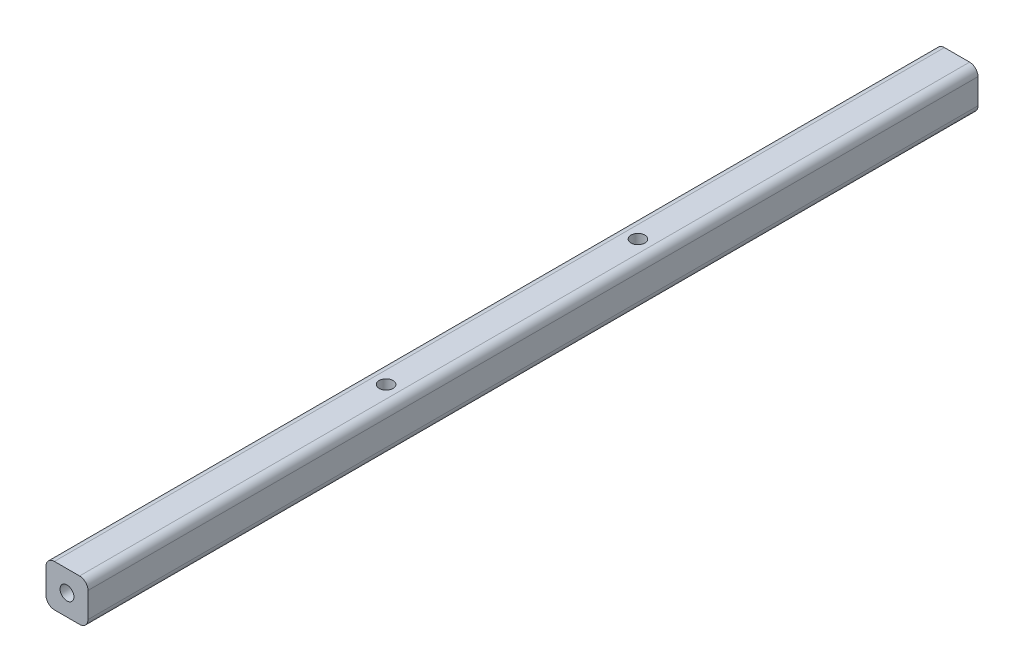
SolidWorks part; units mm, degrees
material "Alliage 1060"
ref_plane "Face" through (0, 0, 0) normal (0, 0, 1) x (1, 0, 0)
ref_plane "Dessus" through (0, 0, 0) normal (0, 1, 0) x (1, 0, 0)
ref_plane "Droite" through (0, 0, 0) normal (1, 0, 0) x (0, 0, -1)
sketch "Esquisse1" plane through (0, 0, 0) normal (0, 0, 1) x (1, 0, 0)
  line L1 (-5, 5) -> (5, 5)
  line L2 (-5, 5) -> (-5, -5)
  line L3 (-5, -5) -> (5, -5)
  line L4 (5, 5) -> (5, -5)
extrude "Boss.-Extru.1" add sketch "Esquisse1" along normal mid plane 212
hole_wizard "Trou taraudé M41" positions "Esquisse3" profile "Esquisse2" tap size "M4" standard "Iso"
sketch "Esquisse3" plane through (0, 0, 106) normal (0, 0, 1) x (1, 0, 0)
  point P0 (0, 0)
sketch "Esquisse2" plane through (0, 0, 106) normal (1, 0, 0) x (0, -1, 0)
  line L0 (0, 0) -> (0, 12.4914)
  line L1 (0, 12.4914) -> (1.65, 11.5)
  line L2 (1.65, 11.5) -> (1.65, 0)
  line L5 (1.65, 0) -> (0, 0)
  line L10 (0, 12.4914) -> (-1.65, 11.5) construction
  line L11 (0, -6.35) -> (0, 107.95) construction
  dimension "Diamètre du trou pour taraudage" = 3.3
  dimension "Profondeur du trou pour taraudage" = 11.5
  dimension "Angle de pointe" = 118
cosmetic thread "Filetage de perçage1" parameters "D1"=8, "D2"=4
hole_wizard "Trou taraudé M42" positions "Esquisse5" profile "Esquisse4" tap size "M4" standard "Iso"
sketch "Esquisse5" plane through (0, 0, -106) normal (0, 0, -1) x (-1, 0, 0)
  point P0 (0, 0)
sketch "Esquisse4" plane through (0, 0, -106) normal (1, 0, 0) x (0, 1, 0)
  line L0 (0, 0) -> (0, 12.4914)
  line L1 (0, 12.4914) -> (1.65, 11.5)
  line L2 (1.65, 11.5) -> (1.65, 0)
  line L5 (1.65, 0) -> (0, 0)
  line L10 (0, 12.4914) -> (-1.65, 11.5) construction
  line L11 (0, -6.35) -> (0, 107.95) construction
  dimension "Diamètre du trou pour taraudage" = 3.3
  dimension "Profondeur du trou pour taraudage" = 11.5
  dimension "Angle de pointe" = 118
cosmetic thread "Filetage de perçage2"
fillet "Congé1" radius 2 4 edges at (-5, -5, 0) (5, -5, 0) (-5, 5, 0) (5, 5, 0)
hole_wizard "Trou taraudé M44" positions "Esquisse9" profile "Esquisse8" tap size "M4" standard "Iso" end condition up to next
sketch "Esquisse9" plane through (0, 5, 0) normal (0, 1, 0) x (1, 0, 0)
  point P0 (0, -30)
  point P2 (0, 30)
  dimension "D1" = 30
  dimension "D2" = 30
sketch "Esquisse8" plane through (0, 5, 30) normal (1, 0, 0) x (0, 0, 1)
  line L0 (0, 0) -> (0, 10)
  line L1 (0, 10) -> (1.65, 10)
  line L2 (1.65, 10) -> (1.65, 0)
  line L5 (1.65, 0) -> (0, 0)
  line L11 (0, -6.35) -> (0, 107.95) construction
  dimension "Diamètre du trou pour taraudage jusqu'au prochain" = 3.3
  dimension "Profondeur du trou pour taraudage jusqu'au prochain" = 10
cosmetic thread "Filetage de perçage5"
cosmetic thread "Filetage de perçage6"
